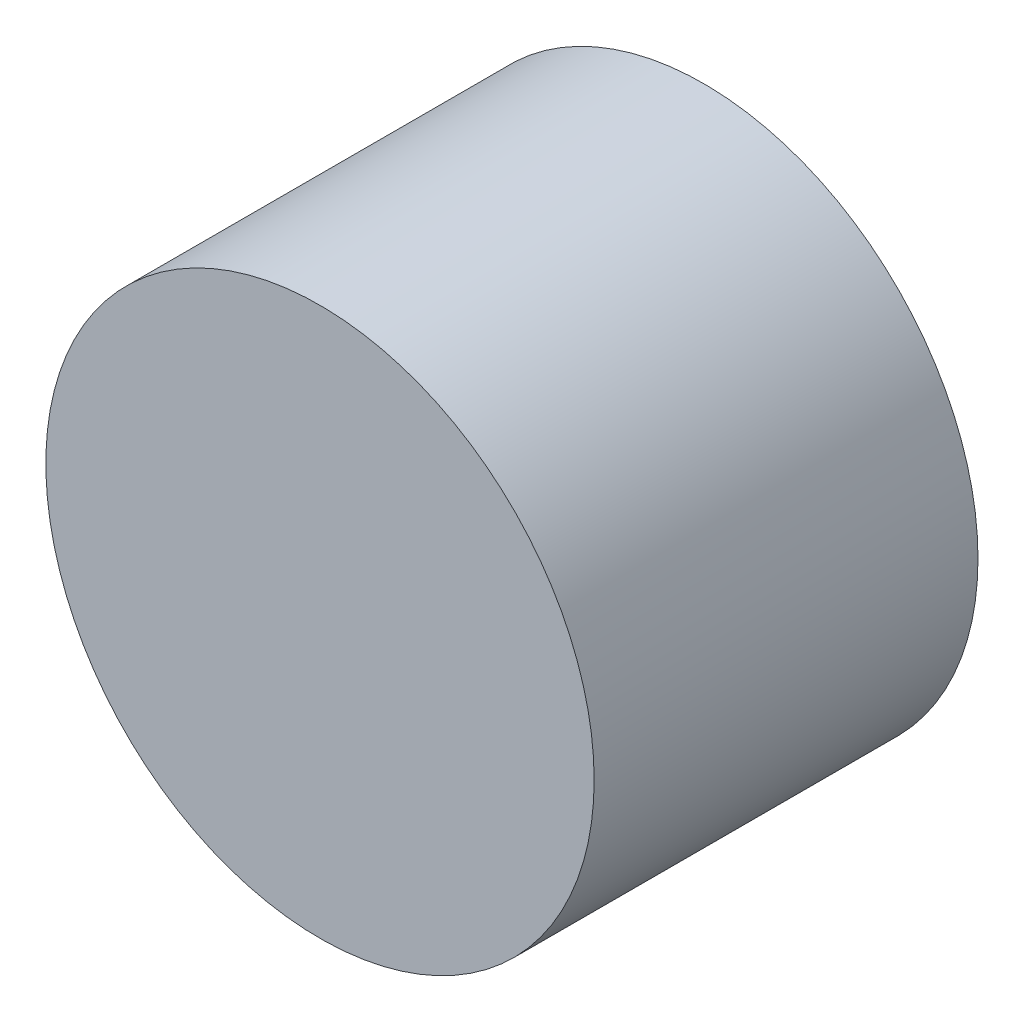
SolidWorks part; units mm, degrees
ref_plane "前视基准面" through (0, 0, 0) normal (0, 0, 1) x (1, 0, 0)
ref_plane "上视基准面" through (0, 0, 0) normal (0, 1, 0) x (1, 0, 0)
ref_plane "右视基准面" through (0, 0, 0) normal (1, 0, 0) x (0, 0, -1)
other "Configuration Table"
sketch "草图1" plane through (0, 0, 0) normal (0, 0, 1) x (1, 0, 0)
  circle A0 centre (0, 0) radius 20
extrude "凸台-拉伸1" add sketch "草图1" along normal blind 28
